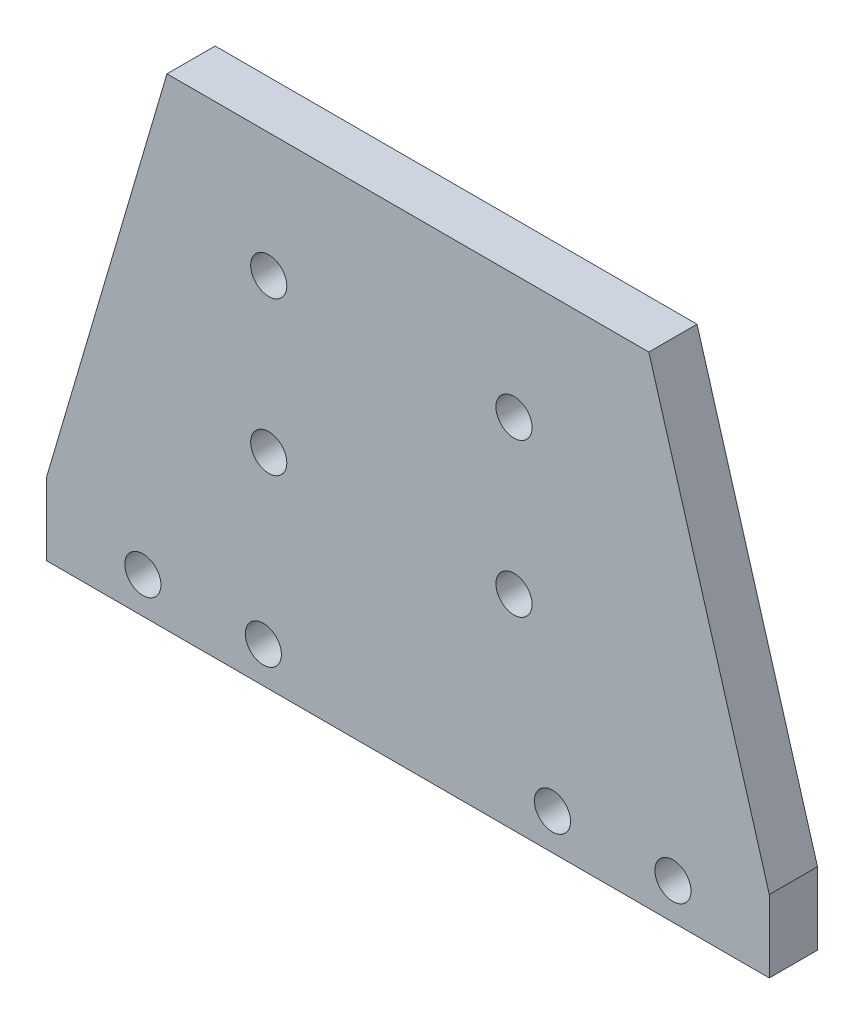
SolidWorks part; units mm, degrees
ref_plane "前视基准面" through (0, 0, 0) normal (0, 0, 1) x (1, 0, 0)
ref_plane "上视基准面" through (0, 0, 0) normal (0, 1, 0) x (1, 0, 0)
ref_plane "右视基准面" through (0, 0, 0) normal (1, 0, 0) x (0, 0, -1)
sketch "草图1" plane through (0, 0, 0) normal (0, 0, 1) x (1, 0, 0)
  line L1 (-30, -20) -> (30, -20)
  line L2 (-30, -20) -> (-30, 20)
  line L3 (-30, 20) -> (30, 20)
  line L4 (30, -20) -> (30, 20)
  line L5 (-30, -20) -> (30, 20) construction
  line L6 (-30, 20) -> (30, -20) construction
  point P0 (0, 0)
  dimension "D1" = 60
  dimension "D2" = 40
extrude "凸台-拉伸1" add sketch "草图1" along normal blind 4
sketch "草图3" plane through (0, 0, 4) normal (0, 0, 1) x (1, 0, 0)
  line L0 (0, 0) -> (0, 21.8826) construction
  line L1 (-30, -14) -> (-20, 20)
  line L2 (-30, 20) -> (-30, -20) construction
  line L3 (30, 20) -> (-30, 20) construction
  line L4 (-30, -20) -> (30, -20) construction
  line L5 (-20, 20) -> (-34.1392, 23.4242)
  line L6 (-34.1392, 23.4242) -> (-38.4637, 14.487)
  line L7 (-38.4637, 14.487) -> (-35.6288, 5.0212)
  line L8 (-35.6288, 5.0212) -> (-34.1392, -14)
  line L9 (35.6288, 5.0212) -> (34.1392, -14)
  line L10 (38.4637, 14.487) -> (35.6288, 5.0212)
  line L11 (34.1392, 23.4242) -> (38.4637, 14.487)
  line L12 (20, 20) -> (34.1392, 23.4242)
  line L13 (30, -14) -> (20, 20)
  line L14 (-30, -14) -> (-34.1392, -14)
  line L15 (34.1392, -14) -> (30, -14)
  dimension "D1" = 6
  dimension "D2" = 20
extrude "切除-拉伸1" cut sketch "草图3" against normal blind 4 and the other way through all
sketch "草图4" plane through (0, 0, 0) normal (0, 0, -1) x (-1, 0, 0)
  circle A0 centre (22, -17) radius 1.5 construction
  circle A1 centre (12, -17) radius 1.5 construction
  circle A2 centre (-12, -17) radius 1.5 construction
  circle A3 centre (-22, -17) radius 1.5 construction
  circle A4 centre (22, -17) radius 1.5
  circle A5 centre (12, -17) radius 1.5
  circle A6 centre (-12, -17) radius 1.5
  circle A7 centre (-22, -17) radius 1.5
extrude "切除-拉伸2" cut sketch "草图4" against normal blind 10
sketch "草图5" plane through (0, 0, 4) normal (0, 0, 1) x (1, 0, 0)
  circle A0 centre (-11.5523, -2.9973) radius 1.5 construction
  circle A1 centre (-11.5523, 9.7163) radius 1.5 construction
  circle A2 centre (8.8078, -2.9973) radius 1.5 construction
  circle A3 centre (8.8078, 9.7163) radius 1.5 construction
  circle A4 centre (-11.5523, -2.9973) radius 1.5
  circle A5 centre (-11.5523, 9.7163) radius 1.5
  circle A6 centre (8.8078, -2.9973) radius 1.5
  circle A7 centre (8.8078, 9.7163) radius 1.5
extrude "切除-拉伸3" cut sketch "草图5" against normal blind 23
